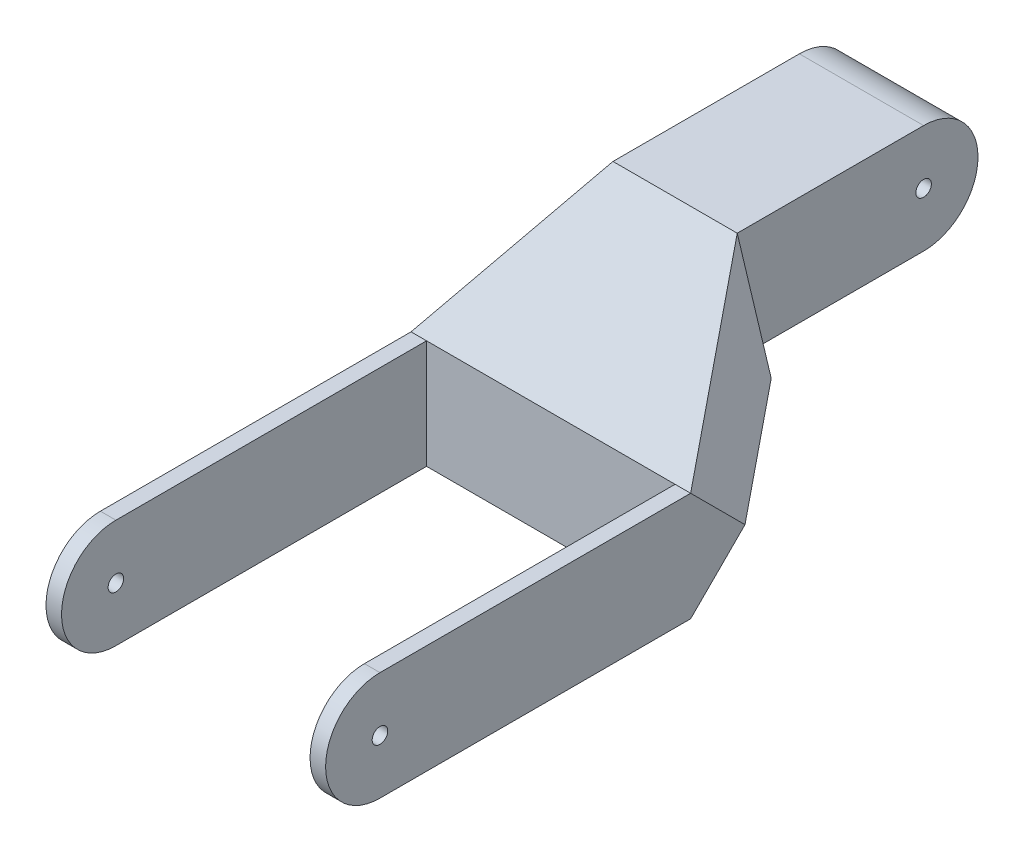
SolidWorks part; units mm, degrees
ref_plane "前视基准面" through (0, 0, 0) normal (0, 0, 1) x (1, 0, 0)
ref_plane "上视基准面" through (0, 0, 0) normal (0, 1, 0) x (1, 0, 0)
ref_plane "右视基准面" through (0, 0, 0) normal (1, 0, 0) x (0, 0, -1)
other "Configuration Table"
sketch "草图1" plane through (0, 0, 0) normal (1, 0, 0) x (0, 0, -1)
  line L1 (6.0355, 5.5899) -> (-13.9645, 5.5899)
  line L2 (6.0355, 5.5899) -> (6.0355, -4.4101)
  line L3 (6.0355, -4.4101) -> (-13.9645, -4.4101)
  line L4 (-13.9645, 5.5899) -> (-13.9645, -4.4101)
  line L5 (6.0355, 5.5899) -> (-13.9645, -4.4101) construction
  line L6 (6.0355, -4.4101) -> (-13.9645, 5.5899) construction
  point P0 (-3.9645, 0.5899)
  dimension "D1" = 20
  dimension "D2" = 10
extrude "凸台-拉伸1" add sketch "草图1" along normal blind 9
sketch "草图2" plane through (9, 0, 0) normal (1, 0, 0) x (0, 0, -1)
  line L2 (-13.9645, -4.4101) -> (-13.9645, -0.9101)
  line L5 (-13.9645, -0.9101) -> (-3.9645, -0.9101)
  line L6 (-13.9645, -4.4101) -> (-3.9645, -4.4101)
  line L8 (-3.9645, -0.9101) -> (0.0355, 3.0899)
  line L9 (0.0355, 3.0899) -> (6.0355, 3.0899)
  line L10 (-13.9645, -4.4101) -> (6.0355, -4.4101) construction
  line L12 (-3.9645, -4.4101) -> (0.0355, -0.4101)
  line L13 (0.0355, -0.4101) -> (6.0355, -0.4101)
  line L14 (6.0355, -4.4101) -> (6.0355, 5.5899) construction
  line L15 (6.0355, -0.4101) -> (6.0355, 3.0899)
  line M14 (-13.9645, -4.4101) -> (6.0355, -4.4101)
  line M15 (6.0355, -4.4101) -> (6.0355, 5.5899)
  dimension "D1" = 3.5
  dimension "D2" = 10
  dimension "D3" = 10
  dimension "D4" = 4
  dimension "D5" = 3.5
extrude "切除-拉伸3" cut sketch "草图2" against normal blind 9 contours L13 L12 M14 M15
sketch "草图6" plane through (9, 0, 0) normal (1, 0, 0) x (0, 0, -1)
  line L0 (-13.9645, -0.9101) -> (-3.9645, -0.9101)
  line L1 (-13.9645, 5.5899) -> (-13.9645, -4.4101) construction
  line L2 (-3.9645, -0.9101) -> (0.0355, 3.0899)
  line L3 (0.0355, 3.0899) -> (6.0355, 3.0899)
  line L4 (6.0355, -0.4101) -> (6.0355, 5.5899) construction
  line L5 (-3.9645, -4.4101) -> (0.0355, -0.4101) construction
  line L6 (0.0355, -0.4101) -> (6.0355, -0.4101) construction
  point P4 (0, 3.0899)
  point P14 (0, 0)
  dimension "D1" = 10
  dimension "D2" = 3.5
extrude "切除-拉伸4" cut sketch "草图6" against normal blind 9 and the other way through all contours L0 L2 L3
sketch "草图8" plane through (9, 0, 0) normal (1, 0, 0) x (0, 0, -1)
  line L0 (-13.9645, -4.4101) -> (-13.9645, -0.9101)
  arc A0 (-13.9645, -0.9101) -> (-13.9645, -4.4101) centre (-13.9645, -2.6601) ccw
extrude "凸台-拉伸2" add sketch "草图8" against normal blind 9
sketch "草图9" plane through (9, 0, 0) normal (1, 0, 0) x (0, 0, -1)
  line L0 (6.0355, -0.4101) -> (6.0355, 3.0899)
  arc A0 (6.0355, 3.0899) -> (6.0355, -0.4101) centre (6.0355, 1.3399) cw
extrude "凸台-拉伸3" add sketch "草图9" against normal blind 9
sketch "草图10" plane through (0, -0.9101, 0) normal (0, 1, 0) x (1, 0, 0)
  line L0 (9, -3.9645) -> (0, -3.9645) construction
  line L1 (8.5, -16.9645) -> (0.5, -16.9645)
  line L2 (8.5, -16.9645) -> (8.5, -3.9645)
  line L3 (8.5, -3.9645) -> (0.5, -3.9645)
  line L4 (0.5, -16.9645) -> (0.5, -3.9645)
  line L5 (8.5, -16.9645) -> (0.5, -3.9645) construction
  line L6 (8.5, -3.9645) -> (0.5, -16.9645) construction
  line L7 (0, -3.9645) -> (0, -13.9645) construction
  point P0 (4.5, -10.4645)
  dimension "D1" = 8
  dimension "D2" = 0.5
  dimension "D3" = 13
extrude "切除-拉伸5" cut sketch "草图10" against normal blind 9
sketch "草图12" plane through (0, 3.0899, 0) normal (0, 1, 0) x (1, 0, 0)
  line L14 (9, 6.0355) -> (9, 0.0355) construction
  line L15 (6.5, 0.0355) -> (9, 0.0355)
  line L17 (6.5, 0.0355) -> (6.5, 12.0355)
  line L18 (6.5, 12.0355) -> (9, 12.0355)
  line L19 (9, 0.0355) -> (9, 12.0355)
  line L20 (6.5, 0.0355) -> (9, 12.0355) construction
  line L21 (6.5, 12.0355) -> (9, 0.0355) construction
  line L22 (9, 0.0355) -> (0, 0.0355) construction
  point P0 (4.5, 4.6422)
  point P1 (4.5, 4.6422)
  point P2 (7.75, 6.0355)
  dimension "D1" = 2.5
  dimension "D2" = 12
  dimension "D3" = 0
extrude "切除-拉伸6" cut sketch "草图12" against normal blind 9
sketch "草图13" plane through (0, 3.0899, 0) normal (0, 1, 0) x (1, 0, 0)
  line L0 (6.5, 0.0355) -> (0, 0.0355) construction
  line L1 (2.5, 0.0355) -> (0, 0.0355)
  line L2 (2.5, 0.0355) -> (2.5, 7.7855)
  line L3 (2.5, 7.7855) -> (0, 7.7855)
  line L4 (0, 0.0355) -> (0, 7.7855)
  line L5 (2.5, 0.0355) -> (0, 7.7855) construction
  line L6 (2.5, 7.7855) -> (0, 0.0355) construction
  point P0 (1.25, 3.9105)
  dimension "D1" = 0
  dimension "D2" = 2.5
extrude "切除-拉伸7" cut sketch "草图13" against normal blind 9
sketch "草图14" plane through (0, 1.5272, 1.5272) normal (0, 0.7071, 0.7071) x (1, 0, 0)
  line L0 (2.5, 2.21) -> (0, -3.4469)
  line L1 (2.5, 2.21) -> (-4.3729, 5.0398)
  line L2 (0, -3.4469) -> (-6.8729, -0.6171)
  line L3 (-4.3729, 5.0398) -> (-6.8729, -0.6171)
extrude "切除-拉伸8" cut sketch "草图14" against normal blind 9
sketch "草图15" plane through (0, 1.5272, 1.5272) normal (0, 0.7071, 0.7071) x (1, 0, 0)
  line L0 (6.5, 2.21) -> (9, -3.4469)
  line L1 (6.5, 2.21) -> (10.1734, 5.6569)
  line L2 (9, -3.4469) -> (12.6734, 0)
  line L3 (10.1734, 5.6569) -> (12.6734, 0)
extrude "切除-拉伸9" cut sketch "草图15" against normal blind 9
sketch "草图18" plane through (6.5, 0, 0) normal (1, 0, 0) x (0, 0, -1)
  circle A0 centre (6.0355, 1.3399) radius 0.25
  dimension "D1" = 0.5
extrude "切除-拉伸12" cut sketch "草图18" against normal through all
sketch "草图25" plane through (0, 0, 3.9645) normal (0, 0, 1) x (1, 0, 0)
  point P0 (4.3043, -2.7547)
sketch "草图26" plane through (0, 0, 0) normal (-1, 0, 0) x (0, 0, 1)
  circle A0 centre (13.9645, -2.6601) radius 0.25
  dimension "D1" = 0.5
extrude "切除-拉伸16" cut sketch "草图26" against normal through all
